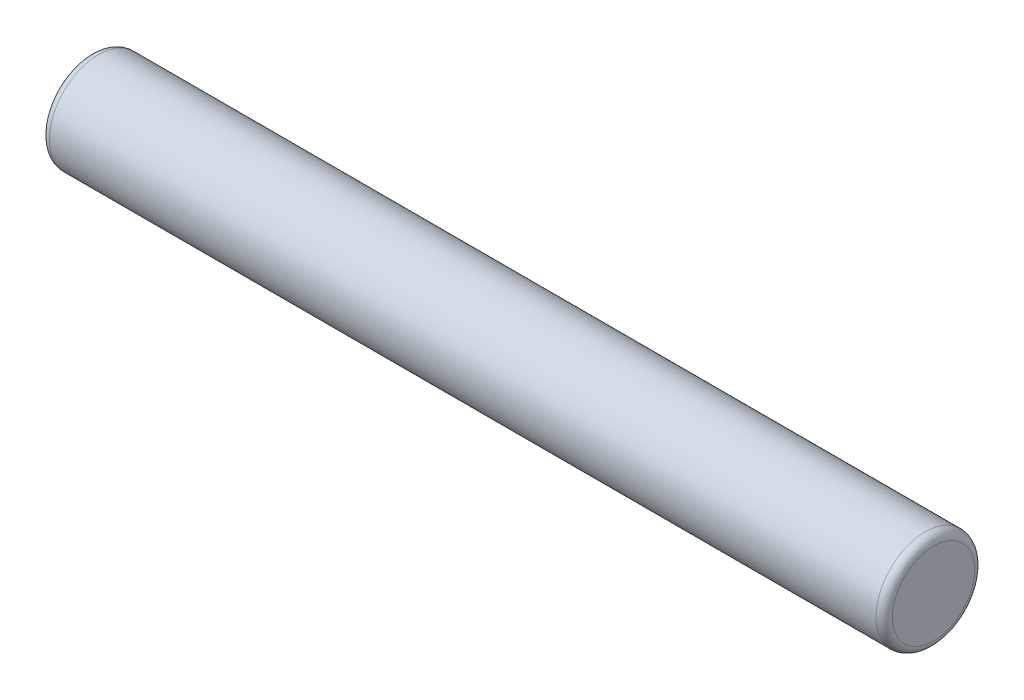
SolidWorks part; units mm, degrees
material "201 軟ｽﾃﾝﾚｽ鋼 (SS)"
ref_plane "正面" through (0, 0, 0) normal (0, 0, 1) x (1, 0, 0)
ref_plane "平面" through (0, 0, 0) normal (0, 1, 0) x (1, 0, 0)
ref_plane "右側面" through (0, 0, 0) normal (1, 0, 0) x (0, 0, -1)
sketch "ｽｹｯﾁ1" plane through (0, 0, 0) normal (1, 0, 0) x (0, 0, -1)
  circle A0 centre (0, 0) radius 1.5
  dimension "D1" = 3
extrude "ﾎﾞｽ - 押し出し1" add sketch "ｽｹｯﾁ1" along normal blind 25.65
fillet "ﾌｨﾚｯﾄ1" radius 0.25 2 edges at (0, 0, -1.5) (25.65, 0, -1.5)
